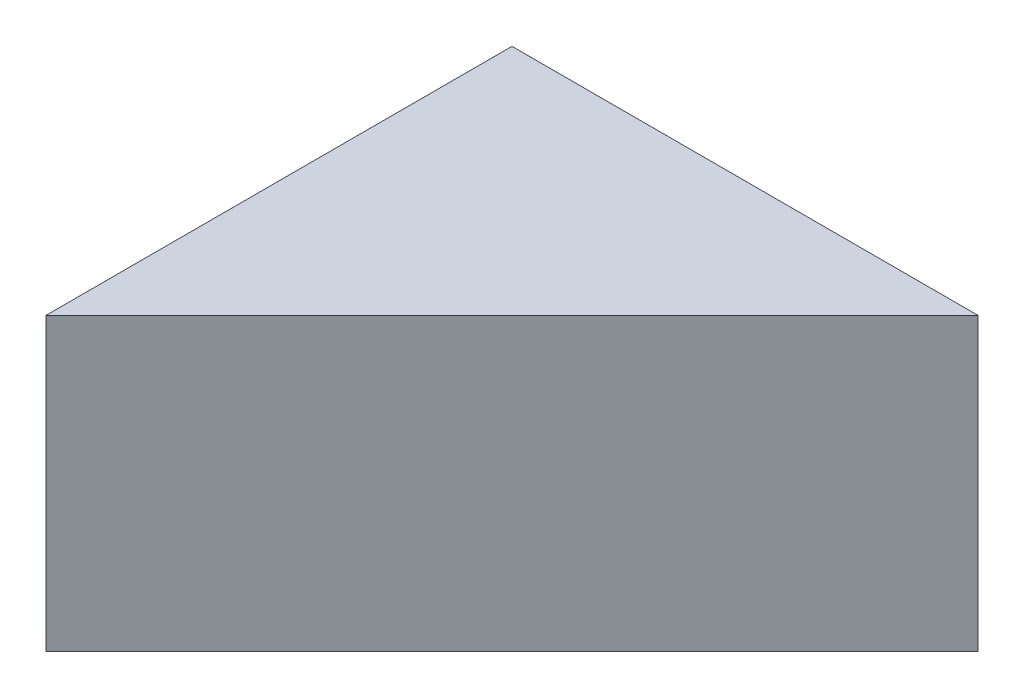
SolidWorks part; units mm, degrees
ref_plane "Front Plane" through (0, 0, 0) normal (0, 0, 1) x (1, 0, 0)
ref_plane "Top Plane" through (0, 0, 0) normal (0, 1, 0) x (1, 0, 0)
ref_plane "Right Plane" through (0, 0, 0) normal (1, 0, 0) x (0, 0, -1)
sketch "Sketch1" plane through (0, 0, 0) normal (0, 1, 0) x (1, 0, 0)
  line L0 (0, -8) -> (0, 8)
  line L1 (0, 8) -> (16, 8)
  line L2 (16, 8) -> (0, -8)
  line L3 (0, 0) -> (8, 0) construction
  line L4 (8, 0) -> (8, 8) construction
  point P4 (0, 0)
  dimension "D1" = 16
  dimension "D3" = 16
extrude "Boss-Extrude1" add sketch "Sketch1" along normal blind 10
